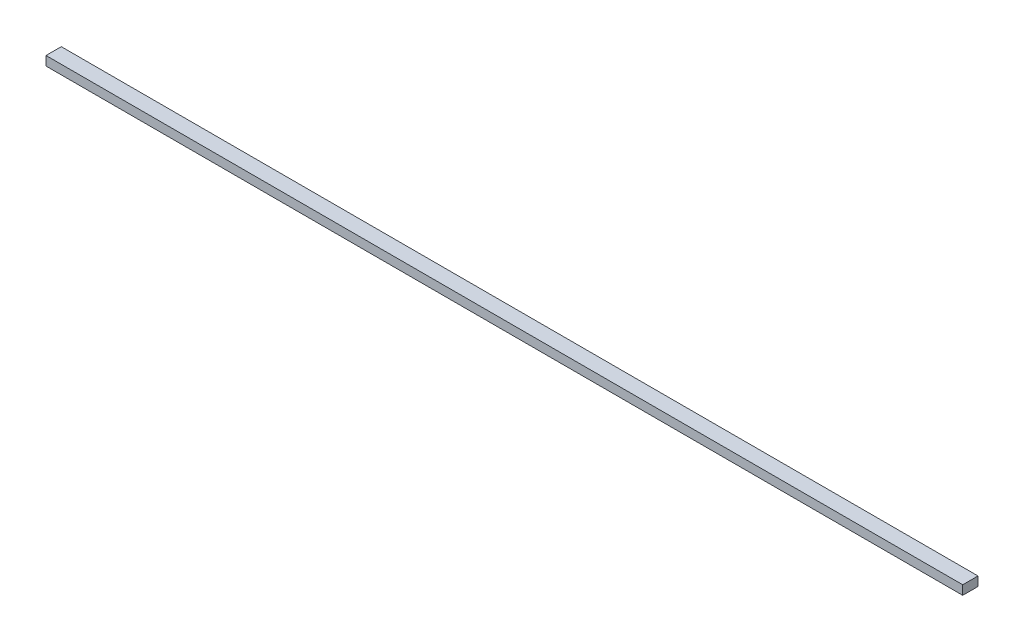
SolidWorks part; units mm, degrees
ref_plane "Front Plane" through (0, 0, 0) normal (0, 0, 1) x (1, 0, 0)
ref_plane "Top Plane" through (0, 0, 0) normal (0, 1, 0) x (1, 0, 0)
ref_plane "Right Plane" through (0, 0, 0) normal (1, 0, 0) x (0, 0, -1)
sketch "Sketch1" plane through (0, 0, 0) normal (0, 1, 0) x (1, 0, 0)
  line L1 (0, 0) -> (300, 0)
  line L2 (0, 0) -> (0, 5)
  line L3 (0, 5) -> (300, 5)
  line L4 (300, 0) -> (300, 5)
  dimension "D1" = 5
  dimension "D2" = 300
extrude "Boss-Extrude1" add sketch "Sketch1" along normal blind 3
